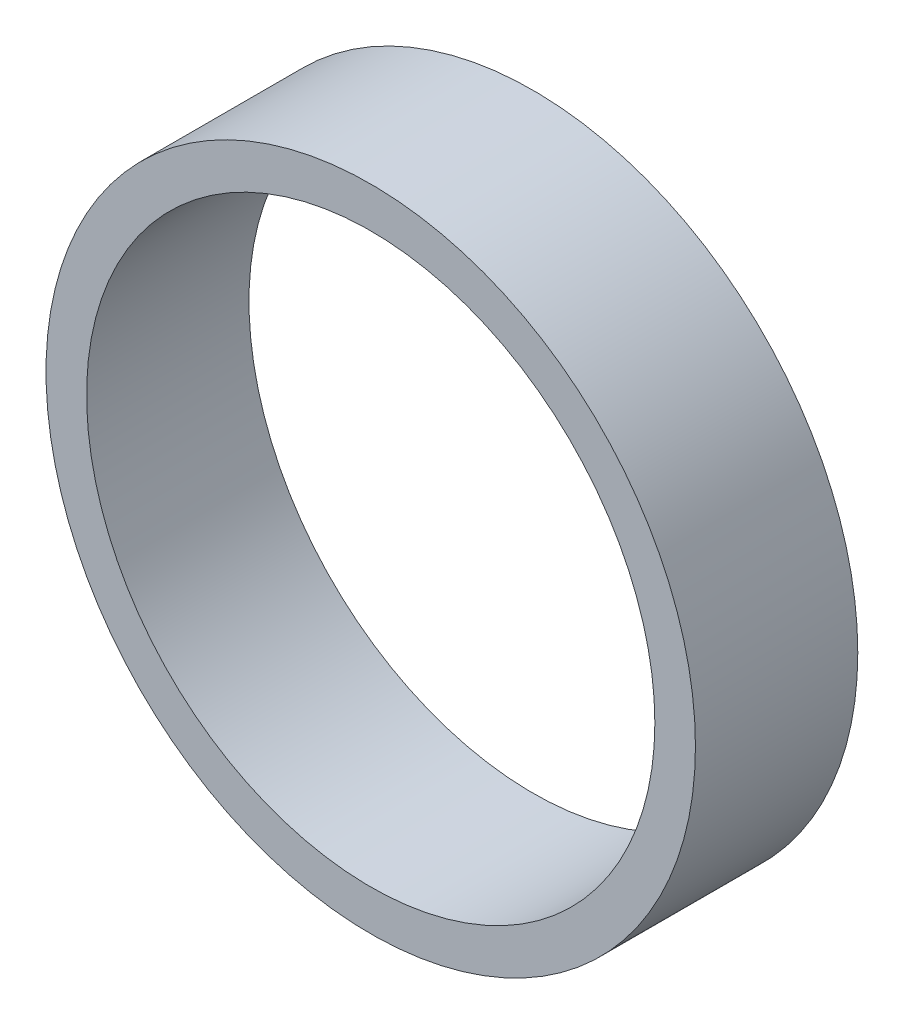
SolidWorks part; units mm, degrees
ref_plane "Front Plane" through (0, 0, 0) normal (0, 0, 1) x (1, 0, 0)
ref_plane "Top Plane" through (0, 0, 0) normal (0, 1, 0) x (1, 0, 0)
ref_plane "Right Plane" through (0, 0, 0) normal (1, 0, 0) x (0, 0, -1)
sketch "Sketch1" plane through (0, 0, 0) normal (0, 0, 1) x (1, 0, 0)
  circle A0 centre (0, 0) radius 12
  circle A1 centre (0, 0) radius 10.5
  dimension "D1" = 24
  dimension "D2" = 21
extrude "Boss-Extrude1" add sketch "Sketch1" along normal blind 6
